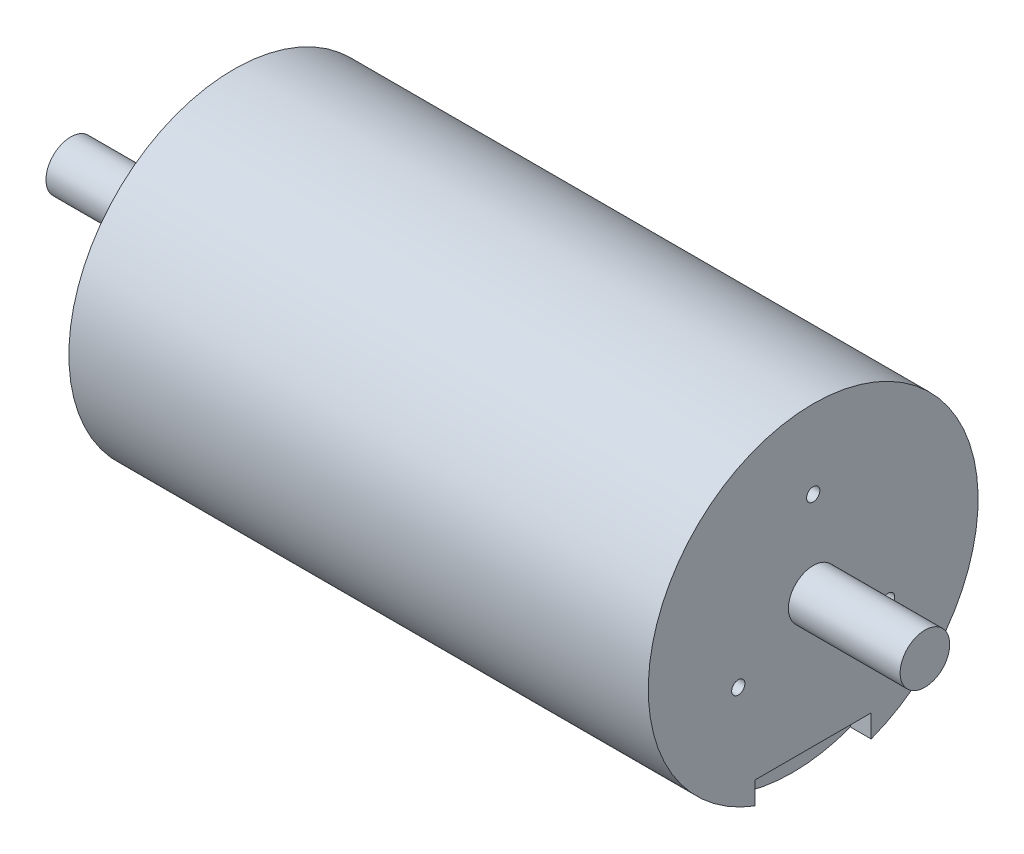
SolidWorks part; units mm, degrees
ref_plane "Front Plane" through (0, 0, 0) normal (0, 0, 1) x (1, 0, 0)
ref_plane "Top Plane" through (0, 0, 0) normal (0, 1, 0) x (1, 0, 0)
ref_plane "Right Plane" through (0, 0, 0) normal (1, 0, 0) x (0, 0, -1)
sketch "Sketch1" plane through (0, 0, 0) normal (1, 0, 0) x (0, 0, -1)
  circle A0 centre (0, 0) radius 2.9945
  dimension "D1" = 5.989
extrude "Extrude1" add sketch "Sketch1" along normal blind 19.7
sketch "Sketch2" plane through (19.7, 0, 0) normal (1, 0, 0) x (0, 0, -1)
  circle A0 centre (0, 0) radius 10.975
  dimension "D1" = 21.95
extrude "Extrude2" add sketch "Sketch2" against normal blind 2.4
sketch "Sketch3" plane through (19.7, 0, 0) normal (1, 0, 0) x (0, 0, -1)
  circle A0 centre (0, 0) radius 19.925
  dimension "D1" = 39.85
extrude "Extrude3" add sketch "Sketch3" along normal blind 70
sketch "Sketch4" plane through (89.7, 0, 0) normal (1, 0, 0) x (0, 0, -1)
  circle A0 centre (0, 0) radius 2.9945
  dimension "D1" = 5.989
extrude "Extrude4" add sketch "Sketch4" along normal blind 13.5
sketch "Sketch5" plane through (19.7, 0, 0) normal (-1, 0, 0) x (0, 0, 1)
  line L0 (0, 0) -> (25.4124, 0)
  line L1 (0, 0) -> (11.3137, 11.3137)
  circle A0 centre (11.3137, 11.3137) radius 1.5
  circle A1 centre (11.3137, -11.3137) radius 1.5
  circle A2 centre (-11.3137, -11.3137) radius 1.5
  circle A3 centre (-11.3137, 11.3137) radius 1.5
  dimension "D3" = 3
  dimension "D1" = 45
  dimension "D2" = 16
extrude "Cut-Extrude1" cut sketch "Sketch5" against normal blind 8
sketch "Sketch6" plane through (89.7, 0, 0) normal (1, 0, 0) x (0, 0, -1)
  line L0 (0, 0) -> (0, 10.45)
  circle A0 centre (0, 10.45) radius 0.8
  circle A1 centre (9.05, -5.225) radius 0.8
  circle A2 centre (-9.05, -5.225) radius 0.8
  dimension "D2" = 1.6
  dimension "D1" = 10.45
extrude "Cut-Extrude2" cut sketch "Sketch6" against normal blind 4
sketch "Sketch7" plane through (89.7, 0, 0) normal (1, 0, 0) x (0, 0, -1)
  line L1 (-7, -15.925) -> (7, -15.925)
  line L2 (-7, -15.925) -> (-7, -18.6549)
  line L3 (7, -15.925) -> (7, -18.6549)
  circle A0 centre (0, 0) radius 19.925 construction
  arc A1 (-7, -18.6549) -> (7, -18.6549) centre (0, 0) ccw
  dimension "D1" = 14
extrude "Cut-Extrude3" cut sketch "Sketch7" against normal blind 2.5
